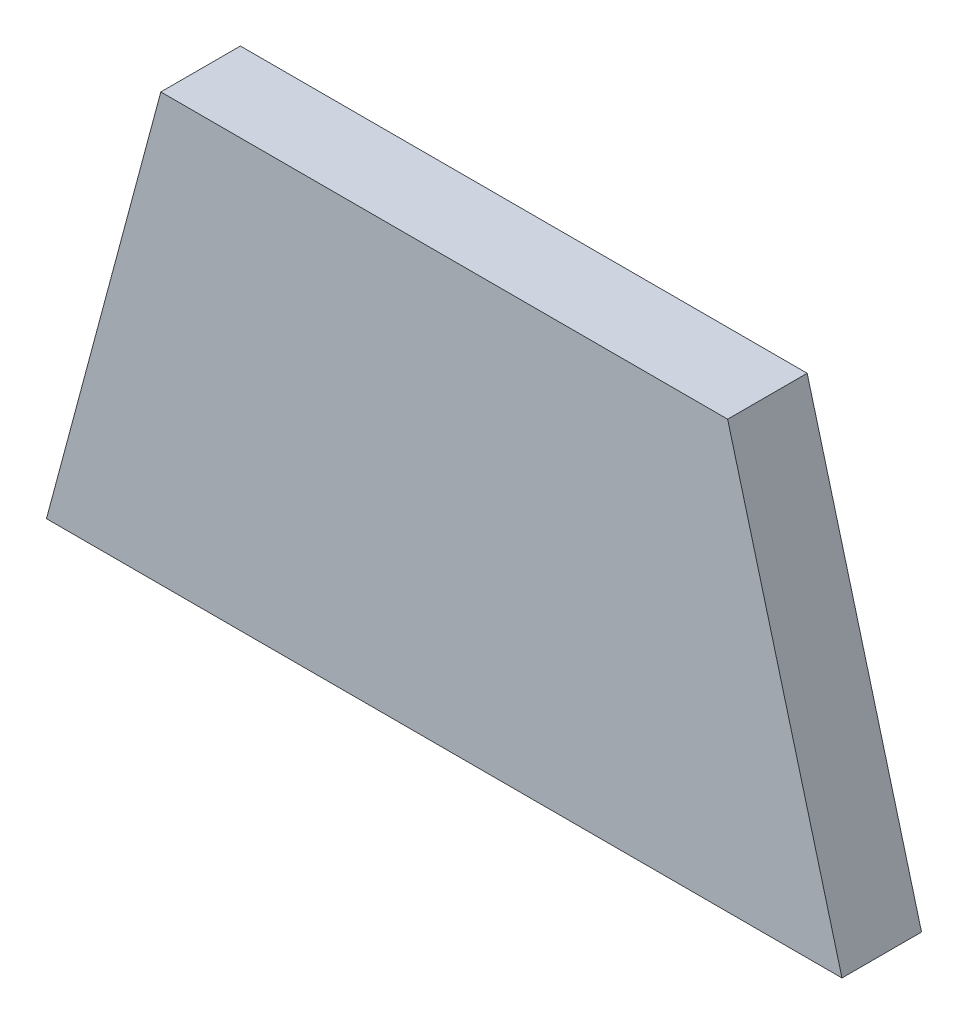
SolidWorks part; units mm, degrees
ref_plane "Alzado" through (0, 0, 0) normal (0, 0, 1) x (1, 0, 0)
ref_plane "Planta" through (0, 0, 0) normal (0, 1, 0) x (1, 0, 0)
ref_plane "Vista lateral" through (0, 0, 0) normal (1, 0, 0) x (0, 0, -1)
sketch "Croquis2" plane through (0, 0, 0) normal (0, 0, 1) x (1, 0, 0)
  line L0 (0, -39.8915) -> (0, 45.6107) construction
  line L1 (90.4875, 136.2665) -> (-90.4875, 136.2665)
  line L2 (-90.4875, 136.2665) -> (-127, 0)
  line L3 (-127, 0) -> (127, 0)
  line L4 (90.4875, 136.2665) -> (127, 0)
  point P8 (0, 0)
  point P9 (0, 136.2665)
  dimension "D1" = 254
  dimension "D2" = 75
  dimension "D3" = 180.975
extrude "Extruir1" add sketch "Croquis2" along normal blind 25.4
